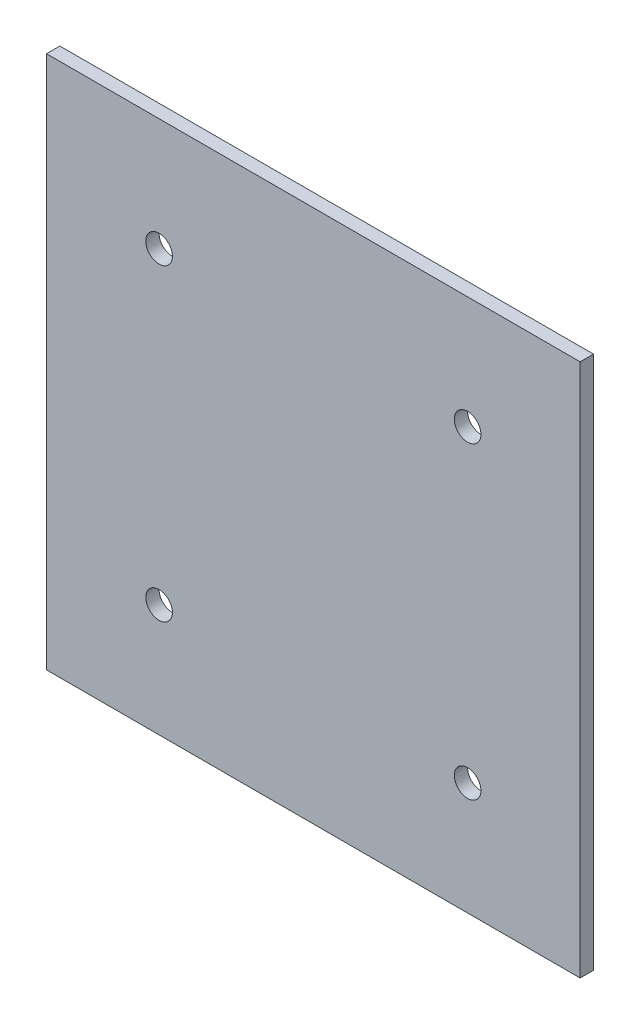
SolidWorks part; units mm, degrees
ref_plane "前视基准面" through (0, 0, 0) normal (0, 0, 1) x (1, 0, 0)
ref_plane "上视基准面" through (0, 0, 0) normal (0, 1, 0) x (1, 0, 0)
ref_plane "右视基准面" through (0, 0, 0) normal (1, 0, 0) x (0, 0, -1)
sketch "草图1" plane through (0, 0, 0) normal (0, 0, 1) x (1, 0, 0)
  line L1 (-32, -32) -> (32, -32)
  line L2 (-32, -32) -> (-32, 32)
  line L3 (-32, 32) -> (32, 32)
  line L4 (32, -32) -> (32, 32)
  line L5 (-32, -32) -> (32, 32) construction
  line L6 (-32, 32) -> (32, -32) construction
  dimension "D1" = 32
  dimension "D2" = 32
  dimension "D3" = 32
extrude "PCB外廓参考_板厚暂按1.6" add sketch "草图1" along normal blind 1.6 from offset 8
sketch "草图2" plane through (0, 0, 0) normal (0, 0, 1) x (1, 0, 0)
  circle A0 centre (-18.5, -18.5) radius 1.6
  circle A1 centre (-18.5, 18.5) radius 1.6
  circle A2 centre (18.5, -18.5) radius 1.6
  circle A3 centre (18.5, 18.5) radius 1.6
  dimension "D1" = 3.2
  dimension "D2" = 18.5
  dimension "D3" = 18.5
  dimension "D4" = 18.5
  dimension "D5" = 18.5
extrude "仅定位参考_原板孔径未给出" cut sketch "草图2" along normal blind 1.6 from offset 8
